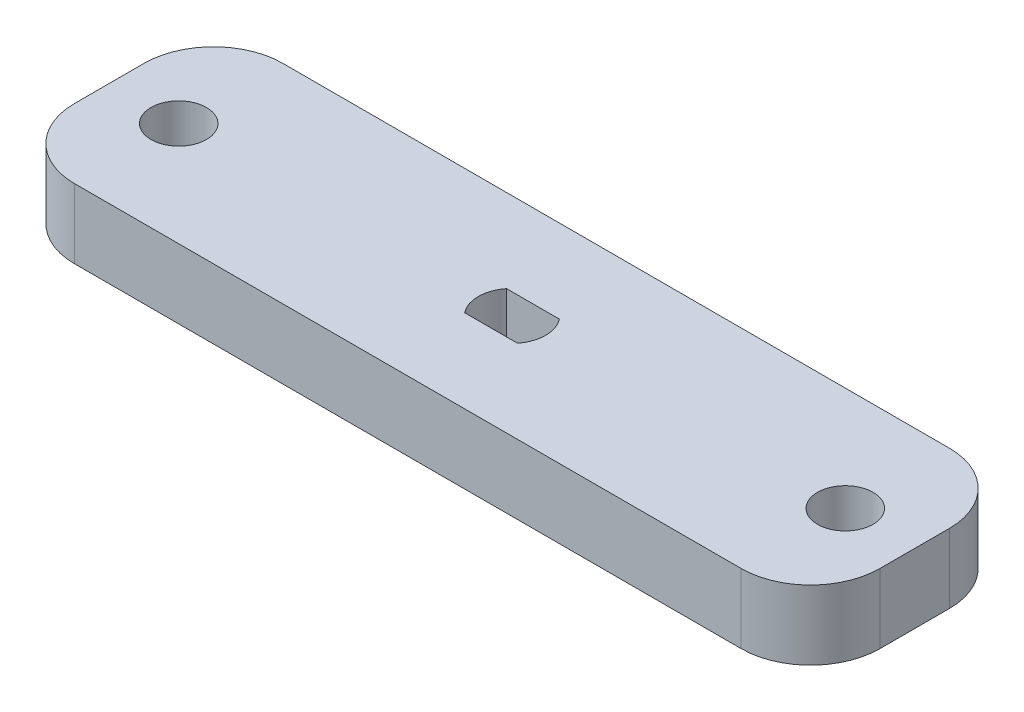
SolidWorks part; units mm, degrees
ref_plane "Front Plane" through (0, 0, 0) normal (0, 0, 1) x (1, 0, 0)
ref_plane "Top Plane" through (0, 0, 0) normal (0, 1, 0) x (1, 0, 0)
ref_plane "Right Plane" through (0, 0, 0) normal (1, 0, 0) x (0, 0, -1)
sketch "Sketch1" plane through (0, 0, 0) normal (0, 1, 0) x (1, 0, 0)
  line L19 (1.9, -1.5069) -> (-1.9, -1.5069)
  line L20 (2.425, 0) -> (-2.425, 0) construction
  line L21 (-29, -7.5) -> (-29, 7.5)
  line L22 (29, -7.5) -> (-29, -7.5)
  line L23 (29, -7.5) -> (29, 7.5)
  line L24 (29, 7.5) -> (-29, 7.5)
  line L26 (1.9, 1.5069) -> (-1.9, 1.5069)
  arc A29 (1.9, -1.5069) -> (1.9, 1.5069) centre (0, 0) ccw
  arc A30 (-1.9, 1.5069) -> (-1.9, -1.5069) centre (0, 0) ccw
  circle A31 centre (24, 0) radius 2
  circle A32 centre (-24, 0) radius 2
  point P12 (0, 0)
  point P14 (29, 0)
  point P33 (0, 0)
  point P37 (0, 0)
  point P43 (0, 0)
  dimension "D1" = 4
  dimension "D2" = 24
  dimension "D3" = 15
  dimension "D4" = 4.85
  dimension "D7" = 3.8
  dimension "D6" = 58
extrude "Boss-Extrude1" add sketch "Sketch1" along normal blind 5
fillet "Fillet1" radius 5 4 edges at (29, 2.5, 7.5) (-29, 2.5, 7.5) (-29, 2.5, -7.5) (29, 2.5, -7.5)
